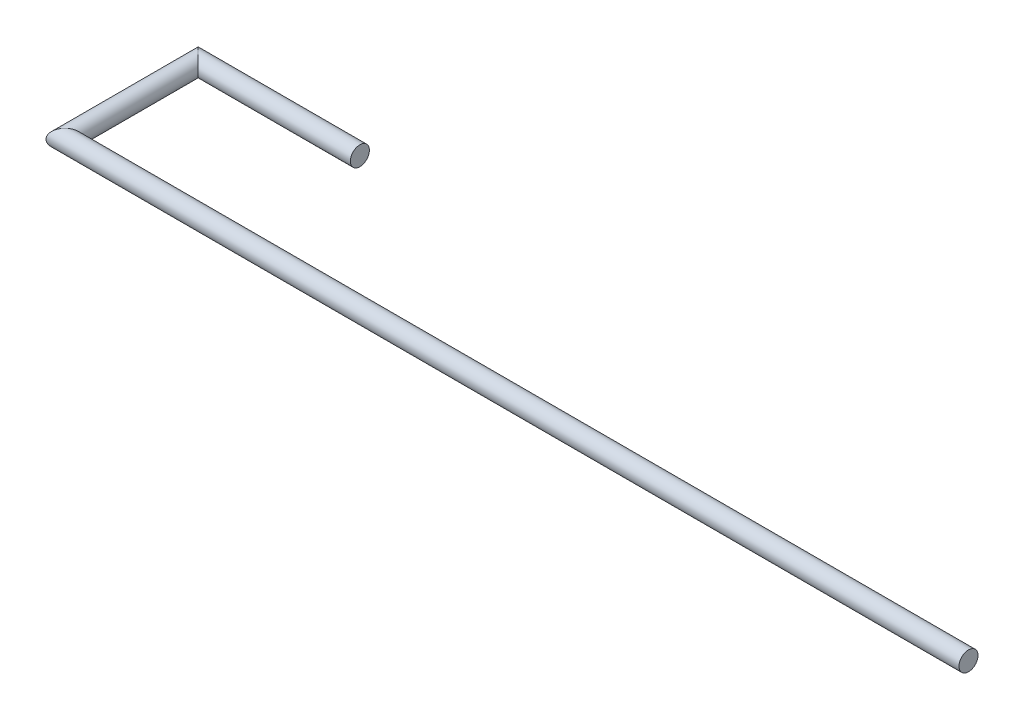
SolidWorks part; units mm, degrees
ref_plane "Front Plane" through (0, 0, 0) normal (0, 0, 1) x (1, 0, 0)
ref_plane "Top Plane" through (0, 0, 0) normal (0, 1, 0) x (1, 0, 0)
ref_plane "Right Plane" through (0, 0, 0) normal (1, 0, 0) x (0, 0, -1)
sketch "Sketch1" plane through (0, 0, 0) normal (0, 1, 0) x (1, 0, 0)
  line L0 (0, 0) -> (40, 0) construction
  line L5 (40, 5) -> (-5.0243, 5) construction
  line L6 (-5.0243, 5) -> (-5.0243, -35) construction
  line L7 (-5.0243, -35) -> (234.9757, -35) construction
  line L8 (234.9757, -35) -> (234.9757, -30) construction
  line L9 (234.9757, -30) -> (0, -30) construction
  line L10 (0, -30) -> (0, 0) construction
  line L11 (40, 5) -> (40, 0) construction
  line L12 (40, 2.5) -> (-2.5, 2.5)
  line L13 (-2.5, 2.5) -> (-2.5, -32.5)
  line L14 (-2.5, -32.5) -> (234.9757, -32.5)
  dimension "D1" = 5
  dimension "D2" = 45.0243
  dimension "D3" = 40
  dimension "D4" = 5
  dimension "D5" = 240
  dimension "D6" = 30
  dimension "D7" = 42.5
  dimension "D8" = 35
sweep "Sweep3" add path "Sketch1" circular profile diameter 5 parameters "D3"=5
